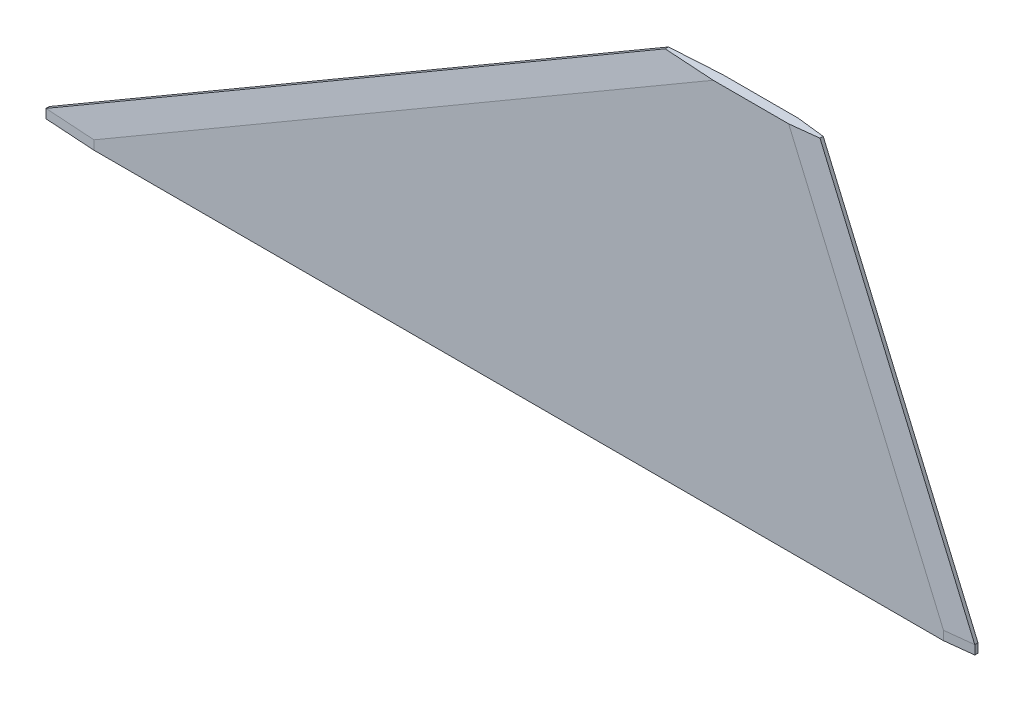
SolidWorks part; units mm, degrees
material "Hexcel AS4C (3000 Filaments)"
ref_plane "Front Plane" through (0, 0, 0) normal (0, 0, 1) x (1, 0, 0)
ref_plane "Top Plane" through (0, 0, 0) normal (0, 1, 0) x (1, 0, 0)
ref_plane "Right Plane" through (0, 0, 0) normal (1, 0, 0) x (0, 0, -1)
sketch "Sketch1" plane through (0, 0, 0) normal (0, 0, 1) x (1, 0, 0)
  line L0 (0, 0) -> (457.2, 0)
  line L1 (457.2, 0) -> (381, 177.8)
  line L2 (381, 177.8) -> (304.8, 177.8)
  line L3 (304.8, 177.8) -> (0, 0)
  dimension "D1" = 457.2
  dimension "D2" = 76.2
  dimension "D3" = 304.8
  dimension "D4" = 177.8
extrude "Boss-Extrude1" add sketch "Sketch1" along normal blind 4.7625
chamfer "Chamfer1" distance 1.5875 distance2 12.7 2 edges at (152.4, 88.9, 0) (152.4, 88.9, 4.7625)
chamfer "Chamfer2" distance 1.5875 distance2 12.7 2 edges at (419.1, 88.9, 0) (419.1, 88.9, 4.7625)
sketch "Sketch2" plane through (0, 0, 0) normal (0, -1, 0) x (1, 0, 0)
  line L8 (25.2049, 0) -> (443.3828, 0)
  line L9 (443.3828, 0) -> (457.2, 1.5875)
  line L10 (457.2, 1.5875) -> (457.2, 3.175)
  line L11 (457.2, 3.175) -> (443.3828, 4.7625)
  line L12 (443.3828, 4.7625) -> (25.2049, 4.7625)
  line L13 (25.2049, 4.7625) -> (0, 3.175)
  line L14 (0, 3.175) -> (0, 1.5875)
  line L15 (0, 1.5875) -> (25.2049, 0)
  line L16 (25.2049, 0) -> (443.3828, 0)
  line L17 (443.3828, 0) -> (457.2, 1.5875)
  line L18 (457.2, 1.5875) -> (457.2, 3.175)
  line L19 (457.2, 3.175) -> (443.3828, 4.7625)
  line L20 (443.3828, 4.7625) -> (25.2049, 4.7625)
  line L21 (25.2049, 4.7625) -> (0, 3.175)
  line L22 (0, 3.175) -> (0, 1.5875)
  line L23 (0, 1.5875) -> (25.2049, 0)
  dimension "D1" = 0
extrude "Boss-Extrude2" add sketch "Sketch2" along normal blind 4.445
sketch "Base Centerline" plane through (0, -4.445, 0) normal (0, -1, 0) x (1, 0, 0)
  line L0 (0, 2.3812) -> (457.2, 2.3812) construction
  line L1 (0, 3.175) -> (0, 1.5875) construction
  line L2 (457.2, 1.5875) -> (457.2, 3.175) construction
sketch "Sketch3" plane through (0, 0, 4.7625) normal (0, 0, 1) x (1, 0, 0)
  line L0 (144.78, 84.455) -> (169.9849, 84.455) construction
  line L1 (0, 0) -> (304.8, 177.8) construction
  line L2 (381, 177.8) -> (457.2, 0) construction
  line L3 (443.3828, 0) -> (367.1828, 177.8) construction
  line L4 (330.0049, 177.8) -> (25.2049, 0) construction
  line L5 (443.3828, 0) -> (367.1828, 177.8)
  line L6 (330.0049, 177.8) -> (25.2049, 0)
  line L7 (0, -4.445) -> (457.2, -4.445) construction
  line L8 (407.1878, 84.455) -> (421.005, 84.455) construction
  point P14 (157.3824, 84.455)
  dimension "D1" = 88.9
